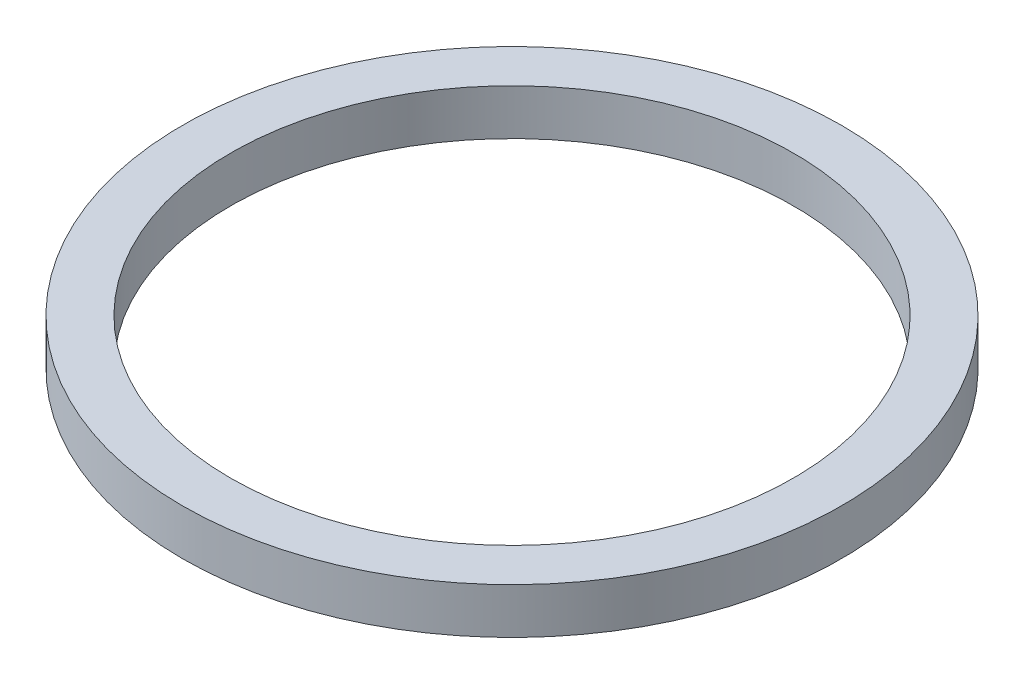
SolidWorks part; units mm, degrees
ref_plane "Front Plane" through (0, 0, 0) normal (0, 0, 1) x (1, 0, 0)
ref_plane "Top Plane" through (0, 0, 0) normal (0, 1, 0) x (1, 0, 0)
ref_plane "Right Plane" through (0, 0, 0) normal (1, 0, 0) x (0, 0, -1)
sketch "Sketch1" plane through (0, 0, 0) normal (0, 1, 0) x (1, 0, 0)
  circle A0 centre (0, 0) radius 3.075
  circle A1 centre (0, 0) radius 3.6
  dimension "D1" = 6.15
  dimension "D2" = 7.2
extrude "Boss-Extrude1" add sketch "Sketch1" along normal blind 0.5
